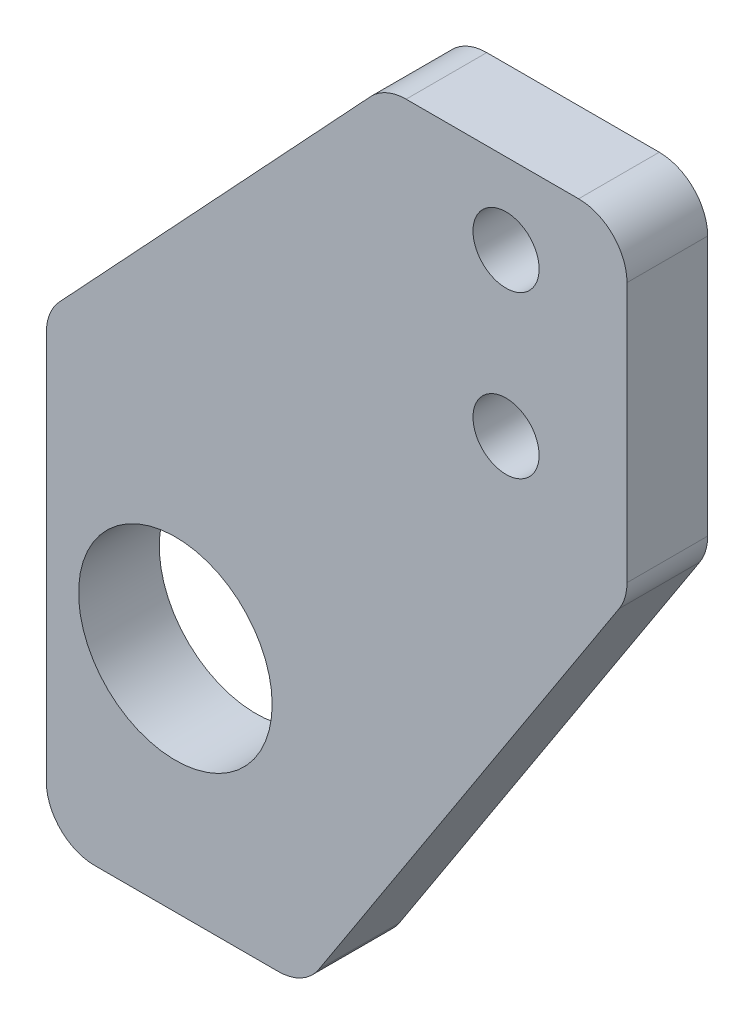
SolidWorks part; units mm, degrees
material "ﾎﾟﾘ塩化ﾋﾞﾆﾙ(PVC)硬質"
ref_plane "正面" through (0, 0, 0) normal (0, 0, 1) x (1, 0, 0)
ref_plane "平面" through (0, 0, 0) normal (0, 1, 0) x (1, 0, 0)
ref_plane "右側面" through (0, 0, 0) normal (1, 0, 0) x (0, 0, -1)
sketch "ｽｹｯﾁ1" plane through (0, 0, 0) normal (0, 0, 1) x (1, 0, 0)
  line L0 (-7.5, 50.8) -> (-7.5, 0) construction
  line L1 (0, 0) -> (-36, 0)
  line L2 (0, 0) -> (0, 50.8)
  line L3 (0, 50.8) -> (-36, 50.8)
  line L4 (-36, 0) -> (-36, 50.8)
  line L5 (0, 30.8) -> (-20, 0)
  line L6 (-20, 0) -> (-36, 0) construction
  line L7 (-20, 0) -> (-20, 28.3) construction
  line L8 (-20, 28.3) -> (-36, 28.3) construction
  line L9 (-36, 0) -> (-36, 28.3) construction
  line L10 (-20, 0) -> (-36, 28.3) construction
  line L11 (-20, 28.3) -> (-36, 0) construction
  line L12 (-36, 28.3) -> (-15, 50.8)
  circle A0 centre (-7.5, 45.8) radius 2.05
  circle A1 centre (-7.5, 35.8) radius 2.05
  circle A2 centre (-28, 14.15) radius 6
  point P12 (-28, 14.15)
  dimension "D1" = 5
  dimension "D2" = 10
  dimension "D3" = 7.5
  dimension "D4" = 4.1
  dimension "D9" = 12
  dimension "D10" = 5
  dimension "D5" = 28.3
  dimension "D6" = 16
  dimension "D7" = 12.5
  dimension "D8" = 7.5
  dimension "D11" = 7.5
extrude "ﾎﾞｽ - 押し出し1" add sketch "ｽｹｯﾁ1" along normal blind 5 contours L12 L4 L1 L5 L2 L3 A2 A1 A0
fillet "ﾌｨﾚｯﾄ1" radius 3 6 edges at (-20, 0, 2.5) (-36, 0, 2.5) (-36, 28.3, 2.5) (-15, 50.8, 2.5) (0, 30.8, 2.5) (0, 50.8, 2.5)
